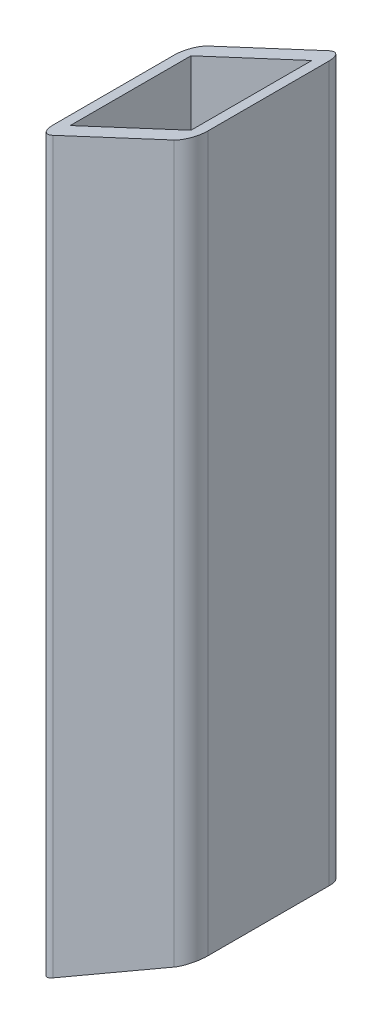
SolidWorks part; units mm, degrees
material "Plain Carbon Steel"
ref_plane "Front Plane" through (0, 0, 0) normal (0, 0, 1) x (1, 0, 0)
ref_plane "Top Plane" through (0, 0, 0) normal (0, 1, 0) x (1, 0, 0)
ref_plane "Right Plane" through (0, 0, 0) normal (1, 0, 0) x (0, 0, -1)
sketch "Sketch1" plane through (0, 0, 0) normal (0, 1, 0) x (1, 0, 0)
  line L1 (2.8, 0) -> (22.8, 0)
  line L2 (0, -2.8) -> (0, -22.8)
  line L3 (2.8, -25.6) -> (22.8, -25.6)
  line L4 (25.6, -2.8) -> (25.6, -22.8)
  arc A0 (22.8, 0) -> (25.6, -2.8) centre (22.8, -2.8) cw
  arc A1 (22.8, -25.6) -> (25.6, -22.8) centre (22.8, -22.8) ccw
  arc A2 (0, -22.8) -> (2.8, -25.6) centre (2.8, -22.8) ccw
  arc A3 (2.8, 0) -> (0, -2.8) centre (2.8, -2.8) ccw
  point P7 (25.6, 0)
  point P10 (25.6, -25.6)
  point P15 (0, 0)
  dimension "D2" = 2.8
  dimension "D1" = 25.6
extrude "Boss-Extrude1" add sketch "Sketch1" along normal blind 133
sketch "Sketch3" plane through (0, 0, 0) normal (0, -1, 0) x (-1, 0, 0)
  line L4 (-2.8, -2.8) -> (-22.8, -2.8)
  line L5 (-2.8, -2.8) -> (-2.8, -22.8)
  line L6 (-2.8, -22.8) -> (-22.8, -22.8)
  line L7 (-22.8, -2.8) -> (-22.8, -22.8)
  line L8 (-2.8, -2.8) -> (-22.8, -22.8) construction
  line L9 (-2.8, -22.8) -> (-22.8, -2.8) construction
  point P6 (-12.8, -12.8)
extrude "Cut-Extrude1" cut sketch "Sketch3" against normal blind 1040.5
ref_plane "Plane1" through (0, 0, 22.8) normal (0, 0, -1) x (-1, 0, 0)
sketch "Sketch4" plane through (0, 0, 22.8) normal (0, 0, -1) x (-1, 0, 0)
  line L0 (-25.6, 133) -> (0, 121.0625)
  line L1 (0, 133) -> (0, 0) construction
extrude "Cut-Extrude2" cut sketch "Sketch4" against normal through all and the other way through all
sketch "Sketch5" plane through (0, 0, 22.8) normal (0, 0, -1) x (-1, 0, 0)
  line L0 (0, 0) -> (-25.6, 14.7802)
  line L1 (-25.6, 133) -> (-25.6, 0) construction
extrude "Cut-Extrude3" cut sketch "Sketch5" against normal through all and the other way through all
